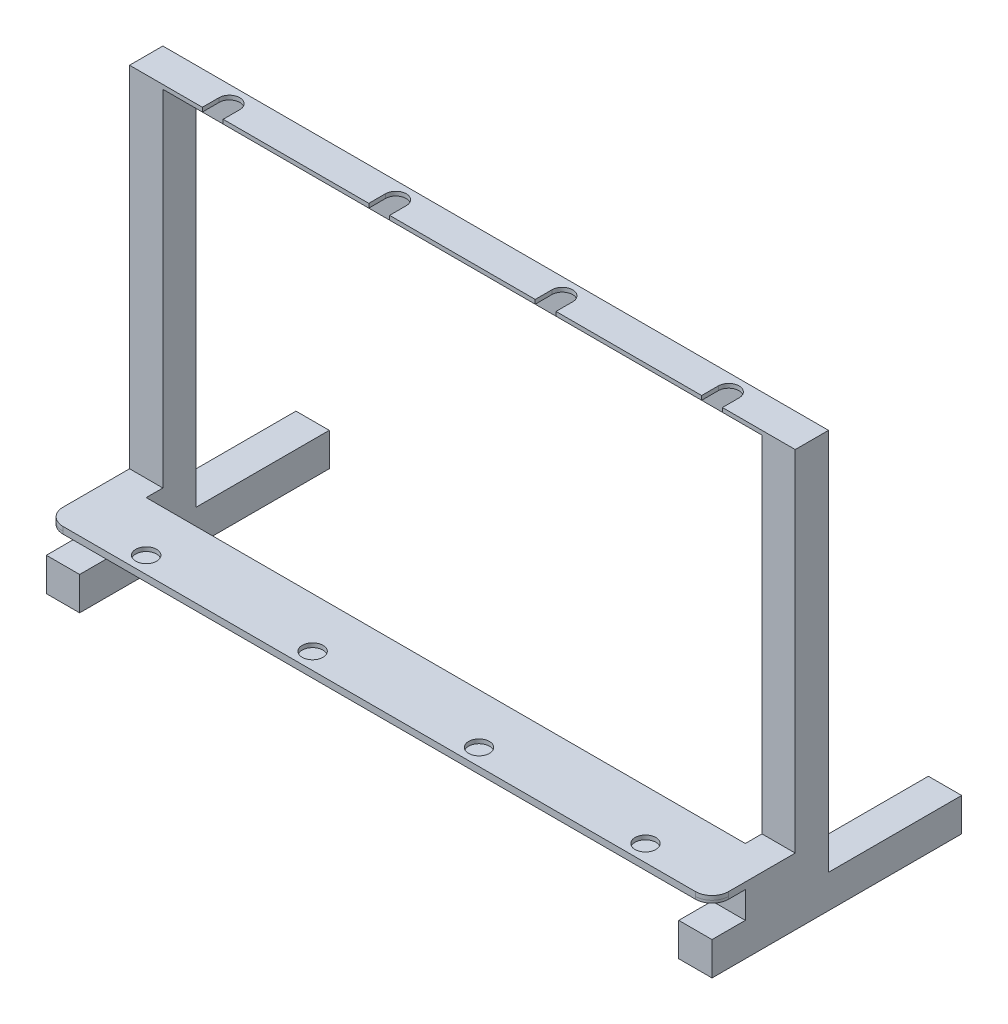
SolidWorks part; units mm, degrees
ref_plane "前视基准面" through (0, 0, 0) normal (0, 0, 1) x (1, 0, 0)
ref_plane "上视基准面" through (0, 0, 0) normal (0, 1, 0) x (1, 0, 0)
ref_plane "右视基准面" through (0, 0, 0) normal (1, 0, 0) x (0, 0, -1)
other "Configuration Table"
sketch "草图1" plane through (0, 0, 0) normal (0, 1, 0) x (1, 0, 0)
  line L0 (-360, 0) -> (360, 0) construction
  line L1 (-400, 160) -> (-360, 160)
  line L2 (-400, 160) -> (-400, -140)
  line L3 (-400, -140) -> (-360, -140)
  line L4 (-360, 160) -> (-360, -140)
  line L5 (360, 160) -> (400, 160)
  line L6 (360, 160) -> (360, -140)
  line L7 (360, -140) -> (400, -140)
  line L8 (400, 160) -> (400, -140)
  dimension "D1" = 160
  dimension "D2" = 40
  dimension "D3" = 300
  dimension "D4" = 720
extrude "凸台-拉伸1" add sketch "草图1" along normal blind 40
sketch "草图2" plane through (0, 40, 0) normal (0, 1, 0) x (1, 0, 0)
  line L0 (-400, -40) -> (-400, -100)
  line L1 (-400, 160) -> (-400, -140) construction
  line L2 (-400, -100) -> (400, -100)
  line L3 (400, -140) -> (400, 160) construction
  line L4 (400, -100) -> (400, -40)
  line L5 (400, -40) -> (360, -40)
  line L6 (360, 160) -> (360, -140) construction
  line L7 (360, -40) -> (360, -60)
  line L8 (360, -60) -> (-360, -60)
  line L9 (-360, -140) -> (-360, 160) construction
  line L10 (-360, -60) -> (-360, -40)
  line L11 (-360, -40) -> (-400, -40)
  line L12 (-400, -140) -> (-360, -140) construction
  dimension "D1" = 60
  dimension "D2" = 40
  dimension "D3" = 100
extrude "凸台-拉伸2" add sketch "草图2" along normal blind 35
sketch "草图3" plane through (0, 75, 0) normal (0, 1, 0) x (1, 0, 0)
  line L0 (-400, -40) -> (-400, -120)
  line L1 (-400, -100) -> (-400, -140) construction
  line L2 (-400, -140) -> (-360, -140) construction
  line L3 (-380, -140) -> (380, -140)
  line L4 (360, -140) -> (400, -140) construction
  line L5 (400, -140) -> (400, -100) construction
  line L6 (400, -120) -> (400, -40)
  line L7 (400, -40) -> (360, -40)
  line L8 (360, -40) -> (360, -60)
  line L9 (360, -60) -> (-360, -60)
  line L10 (-360, -60) -> (-360, -40)
  line L11 (-360, -40) -> (-400, -40)
  line L12 (-400, -120) -> (-300, -120) construction
  line L13 (-300, -120) -> (-100, -120) construction
  line L14 (-100, -120) -> (100, -120) construction
  line L15 (100, -120) -> (300, -120) construction
  line L16 (300, -120) -> (400, -120) construction
  arc A0 (-400, -120) -> (-380, -140) centre (-380, -120) ccw
  arc A1 (380, -140) -> (400, -120) centre (380, -120) ccw
  circle A2 centre (-300, -120) radius 12.5
  circle A3 centre (-100, -120) radius 12.5
  circle A4 centre (100, -120) radius 12.5
  circle A5 centre (300, -120) radius 12.5
  dimension "D1" = 20
  dimension "D3" = 25
  dimension "D2" = 20
  dimension "D4" = 200
  dimension "D5" = 100
extrude "凸台-拉伸3" add sketch "草图3" along normal blind 5
sketch "草图4" plane through (0, 40, 0) normal (0, 1, 0) x (1, 0, 0)
  line L0 (-360, -40) -> (-360, 160) construction
  line L1 (-400, -40) -> (-360, -40)
  line L2 (-400, -40) -> (-400, 0)
  line L3 (-400, 0) -> (-360, 0)
  line L4 (-360, -40) -> (-360, 0)
  line L5 (400, -40) -> (400, 160) construction
  line L6 (360, -40) -> (400, -40)
  line L7 (360, -40) -> (360, 0)
  line L8 (360, 0) -> (400, 0)
  line L9 (400, -40) -> (400, 0)
extrude "凸台-拉伸4" add sketch "草图4" along normal blind 420
sketch "草图5" plane through (0, 460, 0) normal (0, 1, 0) x (1, 0, 0)
  line L0 (-400, 0) -> (-400, -40)
  line L1 (-400, -40) -> (-360, -40)
  line L2 (-360, -40) -> (-360, -5)
  line L3 (-360, -40) -> (-360, 0) construction
  line L4 (-360, -5) -> (360, -5)
  line L5 (360, 0) -> (360, -40) construction
  line L6 (360, -5) -> (360, -40)
  line L7 (360, -40) -> (400, -40)
  line L8 (400, -40) -> (400, 0)
  line L9 (400, 0) -> (-400, 0)
  dimension "D1" = 5
extrude "凸台-拉伸5" add sketch "草图5" along normal blind 35
sketch "草图6" plane through (0, 495, 0) normal (0, 1, 0) x (1, 0, 0)
  line L0 (-400, 0) -> (-400, -40)
  line L1 (-400, -40) -> (-312.5, -40)
  line L2 (-312.5, -40) -> (-312.5, -20)
  line L3 (-287.5, -20) -> (-287.5, -40)
  line L4 (-287.5, -40) -> (-112.5, -40)
  line L5 (-112.5, -40) -> (-112.5, -20)
  line L6 (-87.5, -20) -> (-87.5, -40)
  line L7 (-87.5, -40) -> (87.5, -40)
  line L8 (87.5, -40) -> (87.5, -20)
  line L9 (112.5, -20) -> (112.5, -40)
  line L10 (112.5, -40) -> (287.5, -40)
  line L11 (287.5, -40) -> (287.5, -20)
  line L12 (312.5, -20) -> (312.5, -40)
  line L13 (312.5, -40) -> (400, -40)
  line L14 (400, -40) -> (400, 0)
  line L15 (400, 0) -> (-400, 0)
  line L16 (-300, -20) -> (-100, -20) construction
  line L17 (-100, -20) -> (100, -20) construction
  line L18 (100, -20) -> (300, -20) construction
  line L19 (300, -20) -> (400, -20) construction
  arc A0 (-312.5, -20) -> (-287.5, -20) centre (-300, -20) cw
  arc A1 (-112.5, -20) -> (-87.5, -20) centre (-100, -20) cw
  arc A2 (87.5, -20) -> (112.5, -20) centre (100, -20) cw
  arc A3 (287.5, -20) -> (312.5, -20) centre (300, -20) cw
  dimension "D1" = 25
  dimension "D2" = 20
  dimension "D3" = 100
  dimension "D4" = 200
extrude "凸台-拉伸6" add sketch "草图6" along normal blind 5
sketch "草图7" plane through (0, 75, 0) normal (0, -1, 0) x (1, 0, 0)
  line L0 (-400, 100) -> (400, 100)
  line L1 (400, 100) -> (400, 140)
  line L2 (400, 140) -> (-400, 140)
  line L3 (-400, 140) -> (-400, 100)
extrude "凸台-拉伸7" add sketch "草图7" along normal blind 3
fillet "圆角1" radius 20 2 edges at (400, 73.5, 140) (-400, 73.5, 140)
